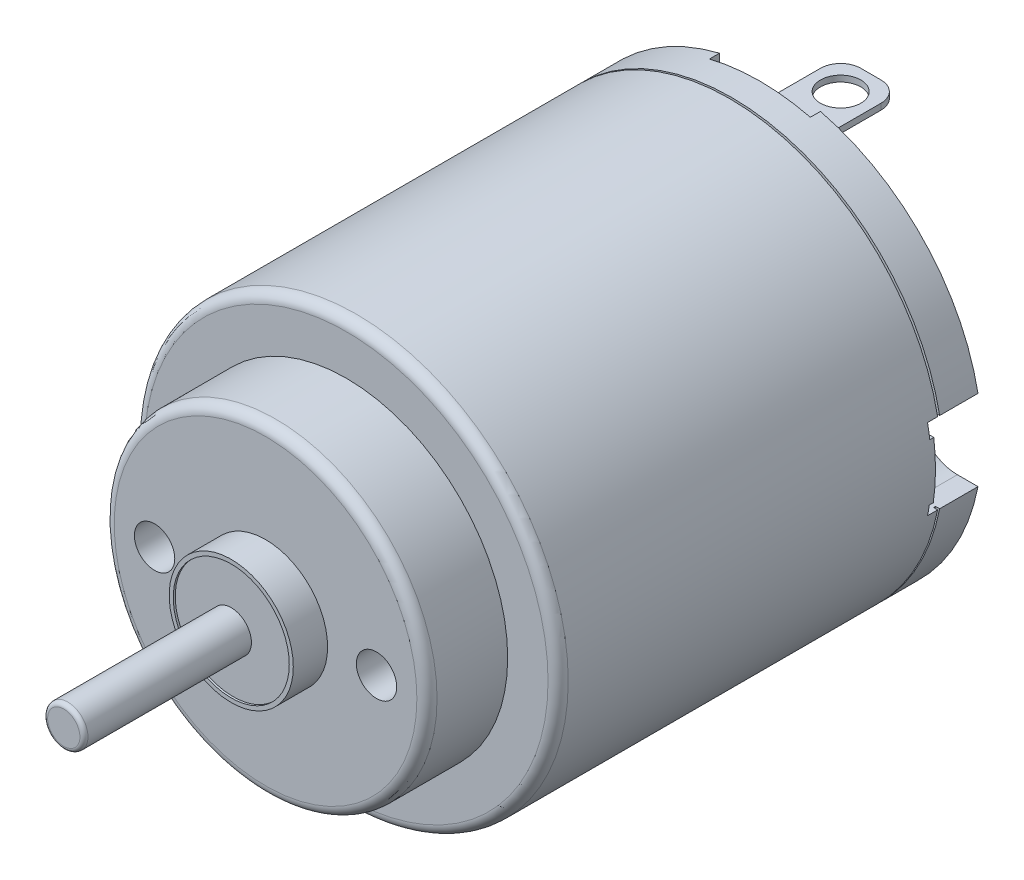
SolidWorks part; units mm, degrees
ref_plane "Plano frontal" through (0, 0, 0) normal (0, 0, 1) x (1, 0, 0)
ref_plane "Plano superior" through (0, 0, 0) normal (0, 1, 0) x (1, 0, 0)
ref_plane "Plano direito" through (0, 0, 0) normal (1, 0, 0) x (0, 0, -1)
sketch "Esboço1" plane through (0, 0, 0) normal (0, 0, 1) x (1, 0, 0)
  circle A0 centre (0, 0) radius 1
  dimension "D1" = 2
extrude "Ressalto-extrusão1" add sketch "Esboço1" along normal blind 38
ref_plane "Plano1" through (0, 0, 28) normal (0, 0, 1) x (1, 0, 0)
sketch "Esboço2" plane through (0, 0, 28) normal (0, 0, 1) x (1, 0, 0)
  circle A0 centre (0, 0) radius 8
  dimension "D1" = 16
extrude "Ressalto-extrusão2" add sketch "Esboço2" against normal blind 25
sketch "Esboço3" plane through (0, 0, 28) normal (0, 0, 1) x (1, 0, 0)
  circle A0 centre (0, 0) radius 3.075
  dimension "D1" = 6.15
extrude "Ressalto-extrusão3" add sketch "Esboço3" along normal blind 1.7
sketch "Esboço4" plane through (0, 0, 3) normal (0, 0, -1) x (-1, 0, 0)
  circle A0 centre (0, 0) radius 10.5
  dimension "D1" = 21
extrude "Ressalto-extrusão4" add sketch "Esboço4" against normal blind 21
sketch "Esboço5" plane through (0, 0, 3) normal (0, 0, -1) x (-1, 0, 0)
  circle A0 centre (0, 0) radius 3.125
  dimension "D1" = 6.25
extrude "Ressalto-extrusão5" add sketch "Esboço5" along normal blind 2
sketch "Esboço6" plane through (0, 0, 3) normal (0, 0, -1) x (-1, 0, 0)
  line L0 (0, 10.5) -> (0, -10.5) construction
  line L2 (1.5, 8.05) -> (-1.5, 8.05)
  line L3 (1.5, 8.05) -> (1.5, 7.75)
  line L4 (1.5, 7.75) -> (-1.5, 7.75)
  line L5 (-1.5, 8.05) -> (-1.5, 7.75)
  line L6 (1.5, 8.05) -> (-1.5, 7.75) construction
  line L7 (1.5, 7.75) -> (-1.5, 8.05) construction
  line L8 (1.5, -7.75) -> (-1.5, -7.75)
  line L9 (1.5, -7.75) -> (1.5, -8.05)
  line L10 (1.5, -8.05) -> (-1.5, -8.05)
  line L11 (-1.5, -7.75) -> (-1.5, -8.05)
  line L12 (1.5, -7.75) -> (-1.5, -8.05) construction
  line L13 (1.5, -8.05) -> (-1.5, -7.75) construction
  circle A0 centre (0, 0) radius 10.5 construction
  point P5 (0, 7.9)
  point P10 (0, -7.9)
  dimension "D1" = 15.5
  dimension "D2" = 0.3
  dimension "D3" = 0.3
  dimension "D4" = 3
  dimension "D5" = 3
  dimension "D6" = 7.75
extrude "Ressalto-extrusão6" add sketch "Esboço6" along normal blind 5
sketch "Esboço7" plane through (0, 8.05, 0) normal (0, 1, 0) x (1, 0, 0)
  line L0 (-1.5, 2) -> (1.5, 2) construction
  circle A0 centre (0, 0.5) radius 1
  point P2 (0, 0.9375)
  point P3 (0, 0.8065)
  dimension "D1" = 2
  dimension "D2" = 1.5
extrude "Corte-extrusão1" cut sketch "Esboço7" against normal blind 4
sketch "Esboço8" plane through (0, -7.75, 0) normal (0, 1, 0) x (1, 0, 0)
  circle A0 centre (0, 0.5) radius 1
extrude "Corte-extrusão2" cut sketch "Esboço8" against normal blind 4
fillet "Filete1" radius 1 4 edges at (1.5, -7.9, -2) (-1.5, -7.9, -2) (1.5, 7.9, -2) (-1.5, 7.9, -2)
fillet "Filete2" radius 0.2 2 edges at (1, 0, 0) (1, 0, 38)
sketch "Esboço9" plane through (0, 0, 3) normal (0, 0, -1) x (-1, 0, 0)
  circle A0 centre (-5.5, 0) radius 1
  circle A1 centre (5.5, 0) radius 1
  dimension "D1" = 11
  dimension "D3" = 2
  dimension "D4" = 2
  dimension "D2" = 5.5
extrude "Corte-extrusão3" cut sketch "Esboço9" against normal blind 38 and the other way blind 15
sketch "Esboço10" plane through (0, 0, 1) normal (0, 0, -1) x (-1, 0, 0)
  line L0 (2.575, 4.4181) -> (2.575, -4.909) construction
  line L2 (2.575, 4.4181) -> (2.575, -4.909)
  line L3 (2.575, -4.909) -> (3.8141, -4.909)
  line L4 (3.8141, -4.909) -> (3.8141, 4.4181)
  line L5 (3.8141, 4.4181) -> (2.575, 4.4181)
extrude "Corte-extrusão4" cut sketch "Esboço10" against normal blind 2
sketch "Esboço11" plane through (0, 0, 3) normal (0, 0, -1) x (-1, 0, 0)
  line L0 (-3.7081, 1.5) -> (-7.3485, 1.5)
  line L1 (7.3485, 1.5) -> (3.7081, 1.5)
  line L3 (7.3485, -1.5) -> (3.7081, -1.5)
  line L5 (-2.5, -7.0711) -> (-2.5, -12.5)
  line L6 (2.5, -7.0711) -> (2.5, -12.5)
  line L7 (-3.7081, -1.5) -> (-7.3485, -1.5)
  line L9 (2.5, 12.5) -> (-2.5, 12.5)
  line L10 (2.5, 12.5) -> (2.5, 7.0711)
  line L11 (2.5, -12.5) -> (-2.5, -12.5)
  line L12 (-2.5, 12.5) -> (-2.5, 7.0711)
  arc A0 (-7.3485, -1.5) -> (-2.5, -7.0711) centre (0, 0) ccw
  circle A1 centre (0, 0) radius 10.5 construction
  arc A2 (-3.7081, -1.5) -> (-2.5, -3.1225) centre (0, 0) ccw
  arc A3 (7.3485, 1.5) -> (2.5, 7.0711) centre (0, 0) ccw
  arc A4 (3.7081, 1.5) -> (2.5, 3.1225) centre (0, 0) ccw
  arc A5 (-2.5, 7.0711) -> (-7.3485, 1.5) centre (0, 0) ccw
  arc A6 (2.5, 3.1225) -> (-3.7081, 1.5) centre (0, 0) ccw
  arc A7 (2.5, -7.0711) -> (7.3485, -1.5) centre (0, 0) ccw
  arc A8 (-2.5, -3.1225) -> (3.7081, -1.5) centre (0, 0) ccw
  point P0 (0, 0)
  dimension "D2" = 3
  dimension "D3" = 8
  dimension "D1" = 5
  dimension "D4" = 25
extrude "Corte-extrusão5" cut sketch "Esboço11" against normal blind 0.5
sketch "Esboço12" plane through (0, 0, 3.5) normal (0, 0, -1) x (-1, 0, 0)
  line L0 (0, 0) -> (0, -6.6243) construction
  line L2 (0, 0) -> (13.3788, 0) construction
  arc A0 (3.375, -5.8457) -> (5.8457, -3.375) centre (0, 0) ccw
  arc A1 (2.375, -4.1136) -> (4.1136, -2.375) centre (0, 0) ccw
  arc A2 (2.375, -4.1136) -> (3.375, -5.8457) centre (2.875, -4.9796) ccw
  arc A3 (4.1136, -2.375) -> (5.8457, -3.375) centre (4.9796, -2.875) cw
  arc A8 (-3.375, 5.8457) -> (-5.8457, 3.375) centre (0, 0) ccw
  arc A9 (-4.1136, 2.375) -> (-5.8457, 3.375) centre (-4.9796, 2.875) cw
  arc A10 (-2.375, 4.1136) -> (-4.1136, 2.375) centre (0, 0) ccw
  arc A11 (-2.375, 4.1136) -> (-3.375, 5.8457) centre (-2.875, 4.9796) ccw
  dimension "D1" = 13.5
  dimension "D2" = 9.5
extrude "Corte-extrusão6" cut sketch "Esboço12" against normal blind 2
sketch "Esboço13" plane through (0, 0, 3) normal (0, 0, 1) x (1, 0, 0)
  line L1 (1.5, 8.05) -> (-1.5, 8.05)
  line L2 (1.5, 8.05) -> (1.5, 7.75)
  line L3 (1.5, 7.75) -> (-1.5, 7.75)
  line L4 (-1.5, 8.05) -> (-1.5, 7.75)
  line L5 (-1.5, -8.05) -> (1.5, -8.05)
  line L6 (-1.5, -8.05) -> (-1.5, -7.75)
  line L7 (-1.5, -7.75) -> (1.5, -7.75)
  line L8 (1.5, -8.05) -> (1.5, -7.75)
extrude "Ressalto-extrusão7" add sketch "Esboço13" along normal blind 6
ref_plane "Plano2" through (0, 0, 5) normal (0, 0, -1) x (-1, 0, 0)
sketch "Esboço14" plane through (0, 0, 5) normal (0, 0, -1) x (-1, 0, 0)
  circle A0 centre (0, 0) radius 11.3093
  circle A1 centre (0, 0) radius 10.3
  arc A2 (-2.5, 10.198) -> (-2.5, -10.198) centre (0, 0) ccw construction
  dimension "D1" = 0.2
extrude "Corte-extrusão7" cut sketch "Esboço14" along normal blind 0.1
fillet "Filete3" radius 0.5 2 edges at (8, 0, 28) (-10.5, 0, 24)
sketch "Esboço15" plane through (0, 0, 29.7) normal (0, 0, 1) x (1, 0, 0)
  circle A0 centre (0, 0) radius 2.875
  circle A1 centre (0, 0) radius 3.075 construction
  dimension "D1" = 0.2
extrude "Corte-extrusão8" cut sketch "Esboço15" against normal blind 0.1
sketch "Esboço16" plane through (0, 0, 3) normal (0, 0, -1) x (-1, 0, 0)
  line L0 (-9.2871, 2) -> (-10.3078, 2)
  line L1 (10.3078, 2) -> (9.2871, 2)
  line L3 (10.3078, -2) -> (9.2871, -2)
  line L7 (-9.2871, -2) -> (-10.3078, -2)
  arc A0 (-2.5, 10.198) -> (-2.5, -10.198) centre (0, 0) ccw construction
  arc A3 (-9.2871, -2) -> (-9.2871, 2) centre (-9.2871, 0) ccw
  arc A4 (9.2871, 2) -> (9.2871, -2) centre (9.2871, 0) ccw
  arc A5 (-10.3078, 2) -> (-10.3078, -2) centre (0, 0) ccw
  arc A6 (10.3078, -2) -> (10.3078, 2) centre (0, 0) ccw
  point P0 (0, 0)
  dimension "D1" = 4
extrude "Corte-extrusão9" cut sketch "Esboço16" against normal blind 2.5
sketch "Esboço17" plane through (0, 0, 5.5) normal (0, 0, -1) x (-1, 0, 0)
  line L0 (-8.5973, 1.3172) -> (-10.417, 1.3172)
  line L1 (10.417, 1.3172) -> (8.5973, 1.3172)
  line L2 (10.417, -1.3172) -> (10.417, -1.5)
  line L3 (10.417, -1.5) -> (8.5666, -1.5)
  line L5 (8.3688, -1.3) -> (8.3951, 1.1172)
  line L6 (10.417, -1.5) -> (10.3928, -1.4965) construction
  line L7 (-8.5973, 1.3172) -> (-8.3951, 1.1172)
  line L8 (-8.3688, -1.3) -> (-8.5666, -1.5)
  line L9 (-8.5666, -1.5) -> (-10.3923, -1.5)
  line L10 (-8.3951, 1.1172) -> (-8.3688, -1.3)
  line L11 (8.5666, -1.5) -> (8.3688, -1.3)
  line L12 (8.5973, 1.3172) -> (8.3951, 1.1172)
  arc A0 (-10.417, 1.3172) -> (-10.3923, -1.5) centre (0, 0) ccw
  arc A2 (10.3923, -1.5) -> (10.417, 1.3172) centre (0, 0) ccw
  point P0 (0, 0)
  point P6 (8.3973, 1.3172)
  point P11 (-8.3973, 1.3172)
  point P13 (-8.3666, -1.5)
  point P14 (8.3666, -1.5)
  arc M6 (-10.3078, 2) -> (-10.3078, -2) centre (0, 0) ccw
extrude "Ressalto-extrusão8" add sketch "Esboço17" along normal blind 0.2 contours L3 A2 L1 L12 L5 L11 | L10 L7 L0 L9 L8 M6
